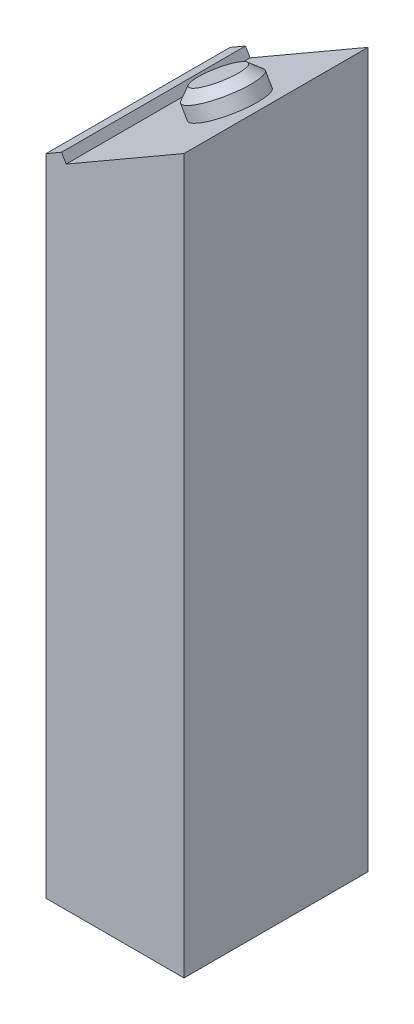
SolidWorks part; units mm, degrees
material "AISI 1010 钢，热轧条材"
ref_plane "前视基准面" through (0, 0, 0) normal (0, 0, 1) x (1, 0, 0)
ref_plane "上视基准面" through (0, 0, 0) normal (0, 1, 0) x (1, 0, 0)
ref_plane "右视基准面" through (0, 0, 0) normal (1, 0, 0) x (0, 0, -1)
sketch "草图1" plane through (0, 0, 0) normal (0, 0, 1) x (1, 0, 0)
  line L0 (-38.8109, -2.7776) -> (-8.5, 14.7224)
  line L1 (0, 0) -> (8.1193, 22.3076) construction
  line L2 (0, 0) -> (0, 20.26) construction
  line L3 (-39.8109, -1.0455) -> (-9.5, 16.4545)
  line L4 (-39.8109, -1.0455) -> (-38.8109, -2.7776)
  line L5 (6.4984, 17.8542) -> (5.8143, 15.9748)
  arc A0 (5.8143, 15.9748) -> (-8.5, 14.7224) centre (0, 0) ccw
  arc A1 (6.4984, 17.8542) -> (-9.5, 16.4545) centre (0, 0) ccw
  dimension "D1" = 34
  dimension "D2" = 35
  dimension "D3" = 20
  dimension "D4" = 2
  dimension "D5" = 60
extrude "凸台-拉伸1" add sketch "草图1" along normal mid plane 18
sketch "草图2" plane through (-9.5, 16.4545, 0) normal (-0.5, 0.866, 0) x (0.866, 0.5, 0)
  line L0 (-35, 0) -> (-17.822, 0) construction
  line L1 (-35, -9) -> (-35, 9) construction
  circle A0 centre (-26, 0) radius 3.5
  dimension "D1" = 7
  dimension "D2" = 9
extrude "切除-拉伸1" cut sketch "草图2" against normal blind 18
sketch "草图3" plane through (0, 0, 0) normal (0, 0, 1) x (1, 0, 0)
  line L0 (-26, 4.6188) -> (-26, -73)
  line L1 (-38.8109, -2.7776) -> (-8.5, 14.7224) construction
  line L2 (-26, -73) -> (-41, -73)
  line L3 (-41, -73) -> (-41, -4.0415)
  line L4 (-26, 4.6188) -> (-41, -4.0415)
  dimension "D1" = 15
  dimension "D2" = 26
  dimension "D3" = 73
extrude "凸台-拉伸2" add sketch "草图3" along normal mid plane 20 separate body
sketch "草图4" plane through (-8.5, 14.7224, 0) normal (-0.5, 0.866, 0) x (0.866, 0.5, 0)
  circle A2 centre (-26, 0) radius 3.5
  circle A3 centre (-26, 0) radius 3.5
  dimension "D1" = 0
extrude "凸台-拉伸3" add sketch "草图4" along normal blind 2.5
chamfer "倒角1" distance 1 angle 45 1 edges at (-35.2977, 2.1375, 0)
sketch "草图6" plane through (0, 0, 0) normal (0, 0, 1) x (1, 0, 0)
  line L0 (-38.8109, -2.7776) -> (-39.3109, -1.9115)
  line L1 (-39.3109, -1.9115) -> (-41, -2.8868)
  line L2 (-38.8109, -2.7776) -> (-41, -4.0415)
  line L3 (-41, -4.0415) -> (-41, -2.8868)
  line L4 (-41, -4.0415) -> (-41, -73) construction
  line L5 (-26, 4.6188) -> (-41, -4.0415) construction
  dimension "D1" = 1
extrude "凸台-拉伸5" add sketch "草图6" along normal mid plane 20
sketch "草图7" plane through (0, 0, 0) normal (0, 0, 1) x (1, 0, 0)
  line L1 (-47.1389, 24.1369) -> (18.0465, 24.1369)
  line L2 (-47.1389, 24.1369) -> (-47.1389, -6.5247)
  line L3 (-47.1389, -6.5247) -> (18.0465, -6.5247)
  line L4 (18.0465, 24.1369) -> (18.0465, -6.5247)
extrude "切除-拉伸2" cut sketch "草图7" against normal mid plane 20
